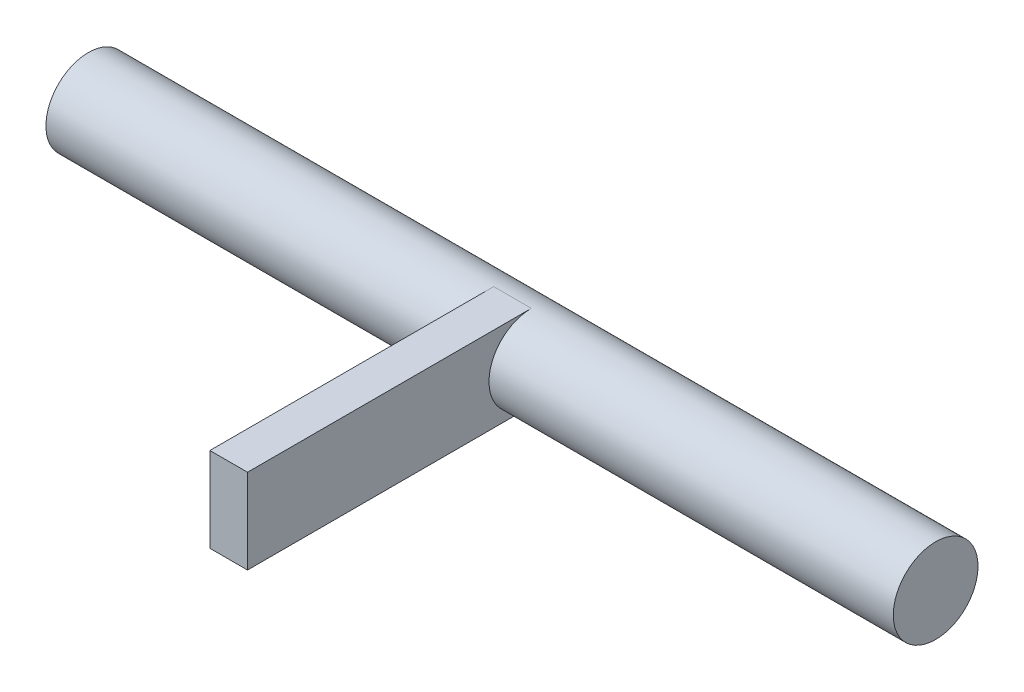
SolidWorks part; units mm, degrees
ref_plane "前视基准面" through (0, 0, 0) normal (0, 0, 1) x (1, 0, 0)
ref_plane "上视基准面" through (0, 0, 0) normal (0, 1, 0) x (1, 0, 0)
ref_plane "右视基准面" through (0, 0, 0) normal (1, 0, 0) x (0, 0, -1)
sketch "草图1" plane through (0, 0, 0) normal (1, 0, 0) x (0, 0, -1)
  circle A0 centre (0, 0) radius 10
extrude "凸台-拉伸1" add sketch "草图1" along normal blind 200
sketch "草图4" plane through (0, 0, 0) normal (0, 0, 1) x (1, 0, 0)
  line L0 (0, -10) -> (200, -10) construction
  line L1 (95.6956, 10) -> (104.5821, 10)
  line L2 (95.6956, 10) -> (95.6956, -10)
  line L3 (95.6956, -10) -> (104.5821, -10)
  line L4 (104.5821, 10) -> (104.5821, -10)
  line L5 (95.6956, 10) -> (104.5821, -10) construction
  line L6 (95.6956, -10) -> (104.5821, 10) construction
  point P0 (100.1389, 0)
  point P7 (-58.2914, -39.3646)
  point P8 (104.5821, 0)
extrude "凸台-拉伸2" add sketch "草图4" along normal blind 67
